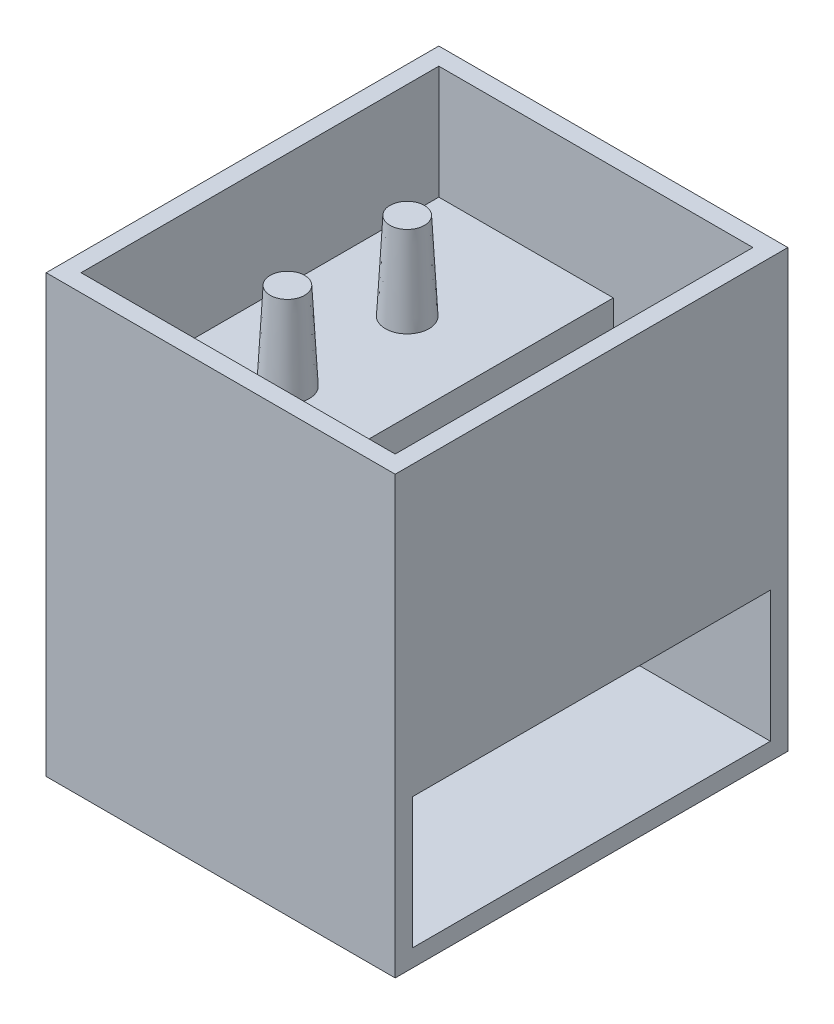
SolidWorks part; units mm, degrees
ref_plane "Front Plane" through (0, 0, 0) normal (0, 0, 1) x (1, 0, 0)
ref_plane "Top Plane" through (0, 0, 0) normal (0, 1, 0) x (1, 0, 0)
ref_plane "Right Plane" through (0, 0, 0) normal (1, 0, 0) x (0, 0, -1)
sketch "Sketch1" plane through (0, 0, 0) normal (0, 1, 0) x (1, 0, 0)
  line L1 (-34.8887, 14.0503) -> (5.1113, 14.0503)
  line L2 (-34.8887, 14.0503) -> (-34.8887, -30.9497)
  line L3 (-34.8887, -30.9497) -> (5.1113, -30.9497)
  line L4 (5.1113, 14.0503) -> (5.1113, -30.9497)
extrude "Boss-Extrude1" add sketch "Sketch1" along normal blind 50
shell "Shell1" thickness 2
sketch "Sketch2" plane through (3.1113, 0, 0) normal (-1, 0, 0) x (0, 0, 1)
  line L1 (-12.0503, 2) -> (28.9497, 2)
  line L2 (-12.0503, 2) -> (-12.0503, 17)
  line L3 (-12.0503, 17) -> (28.9497, 17)
  line L4 (28.9497, 2) -> (28.9497, 17)
extrude "Cut-Extrude1" cut sketch "Sketch2" against normal blind 3
sketch "Sketch3" plane through (-32.8887, 0, 0) normal (1, 0, 0) x (0, 0, -1)
  line L1 (12.0503, 2) -> (-28.9497, 2)
  line L2 (12.0503, 2) -> (12.0503, 27)
  line L3 (12.0503, 27) -> (-28.9497, 27)
  line L4 (-28.9497, 2) -> (-28.9497, 27)
sketch "Sketch4" plane through (-32.8887, 0, 0) normal (1, 0, 0) x (0, 0, -1)
  line L1 (12.0503, 27) -> (-28.9497, 27)
  line L2 (12.0503, 27) -> (12.0503, 37)
  line L3 (12.0503, 37) -> (-28.9497, 37)
  line L4 (-28.9497, 27) -> (-28.9497, 37)
extrude "Boss-Extrude2" add sketch "Sketch4" along normal blind 20
sketch "Sketch5" plane through (0, 37, 0) normal (0, 1, 0) x (1, 0, 0)
  line L1 (-12.8887, 12.0503) -> (-32.8887, 12.0503)
  line L2 (-12.8887, 12.0503) -> (-12.8887, 2.0503)
  line L3 (-12.8887, 2.0503) -> (-32.8887, 2.0503)
  line L4 (-32.8887, 12.0503) -> (-32.8887, 2.0503)
sketch "Sketch7" plane through (0, 37, 0) normal (0, 1, 0) x (1, 0, 0)
  line L0 (-32.8887, 12.0503) -> (-32.8887, -28.9497) construction
  line L1 (-12.8887, -28.9497) -> (-32.8887, -28.9497)
  line L2 (-12.8887, -28.9497) -> (-12.8887, -18.9497)
  line L3 (-12.8887, -18.9497) -> (-32.8887, -18.9497)
  line L4 (-32.8887, -28.9497) -> (-32.8887, -18.9497)
sketch "Sketch8" plane through (0, 37, 0) normal (0, 1, 0) x (1, 0, 0)
  line L1 (-12.8887, 12.0503) -> (-22.8887, 12.0503)
  line L2 (-12.8887, 12.0503) -> (-12.8887, -28.9497)
  line L3 (-12.8887, -28.9497) -> (-22.8887, -28.9497)
  line L4 (-22.8887, 12.0503) -> (-22.8887, -28.9497)
sketch "Sketch15" plane through (0, 37, 0) normal (0, 1, 0) x (1, 0, 0)
  line L0 (-22.8887, 12.0503) -> (-22.8887, -28.9497) construction
  circle A0 centre (-22.8887, -1.5729) radius 3.5
sketch "Sketch16" plane through (0, 37, 0) normal (0, 1, 0) x (1, 0, 0)
  circle A0 centre (-22.8102, -15.3779) radius 3.5
  circle A1 centre (-22.8102, -15.3779) radius 2.5
sketch "Sketch17" plane through (0, 37, 0) normal (0, 1, 0) x (1, 0, 0)
  circle A0 centre (-22.8887, -1.5729) radius 2.5
  circle A1 centre (-22.8102, -15.3779) radius 2.5
extrude "Boss-Extrude3" add sketch "Sketch17" along normal blind 10 draft 3 contours A0
extrude "Boss-Extrude4" add sketch "Sketch16" along normal blind 10 draft 3 contours A1
